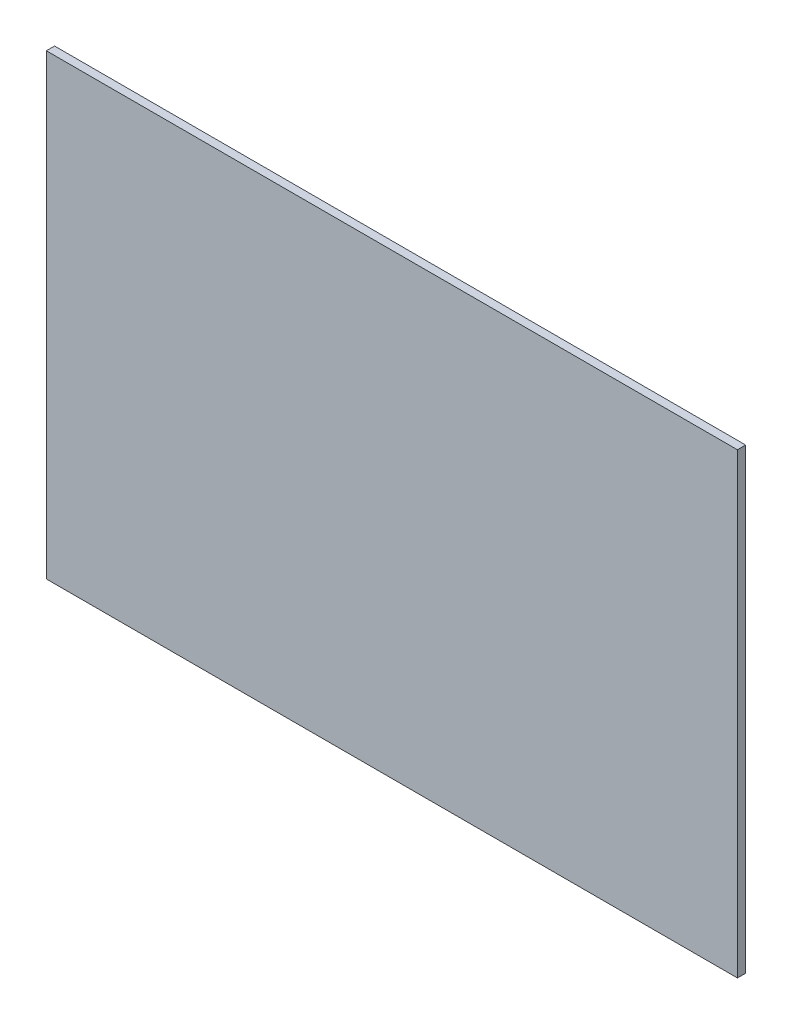
SolidWorks part; units mm, degrees
ref_plane "정면" through (0, 0, 0) normal (0, 0, 1) x (1, 0, 0)
ref_plane "윗면" through (0, 0, 0) normal (0, 1, 0) x (1, 0, 0)
ref_plane "우측면" through (0, 0, 0) normal (1, 0, 0) x (0, 0, -1)
sketch "스케치1" plane through (0, 0, 0) normal (0, 0, 1) x (1, 0, 0)
  line L1 (-210, 139) -> (210, 139)
  line L2 (-210, 139) -> (-210, -139)
  line L3 (-210, -139) -> (210, -139)
  line L4 (210, 139) -> (210, -139)
  line L5 (-210, 139) -> (210, -139) construction
  line L6 (-210, -139) -> (210, 139) construction
  point P0 (0, 0)
  dimension "D1" = 420
  dimension "D2" = 278
extrude "보스-돌출1" add sketch "스케치1" along normal blind 5
